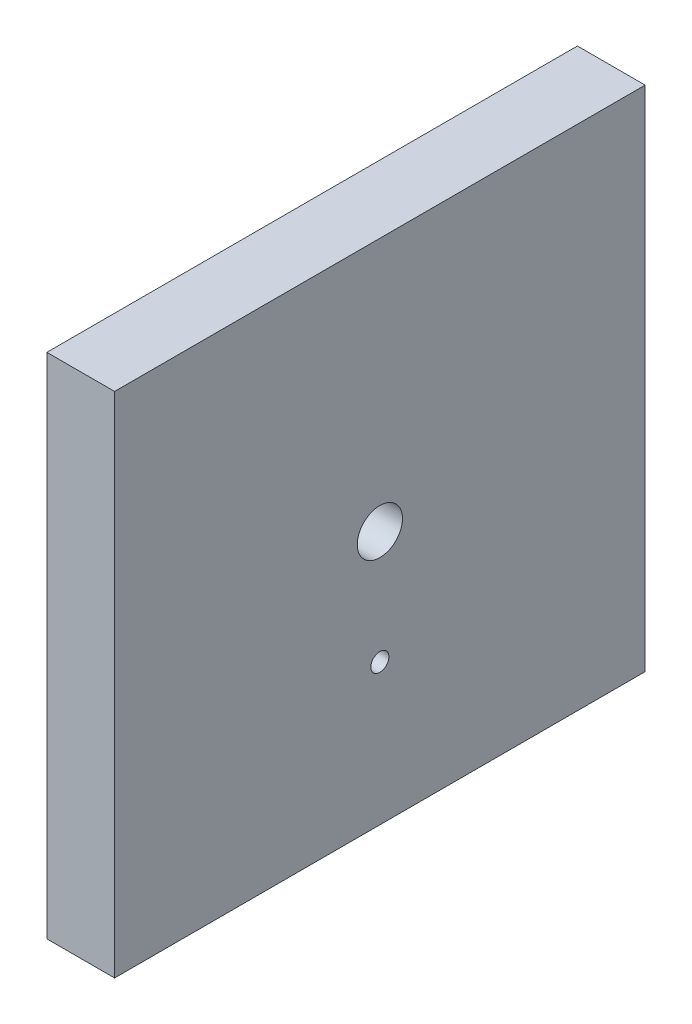
SolidWorks part; units mm, degrees
ref_plane "Ebene vorne" through (0, 0, 0) normal (0, 0, 1) x (1, 0, 0)
ref_plane "Ebene oben" through (0, 0, 0) normal (0, 1, 0) x (1, 0, 0)
ref_plane "Ebene rechts" through (0, 0, 0) normal (1, 0, 0) x (0, 0, -1)
sketch "Sketch1" plane through (0, 0, 0) normal (1, 0, 0) x (0, 0, -1)
  line L0 (0, 39.4227) -> (0, -41.65) construction
  line L1 (-47, 45) -> (47, 45)
  line L2 (-47, 45) -> (-47, -45)
  line L3 (-47, -45) -> (47, -45)
  line L4 (47, 45) -> (47, -45)
  line L5 (48.1091, 0) -> (-28.5091, 0) construction
  dimension "D1" = 94
  dimension "D2" = 90
extrude "Boss-Extrude1" add sketch "Sketch1" along normal blind 12
sketch "Sketch2" plane through (12, 0, 0) normal (1, 0, 0) x (0, 0, -1)
  circle A0 centre (0, 0) radius 4
  dimension "D1" = 8
extrude "Cut-Extrude1" cut sketch "Sketch2" against normal through all
sketch "Sketch3" plane through (0, 0, 0) normal (-1, 0, 0) x (0, 0, 1)
  circle A0 centre (0, -20) radius 1.6
  dimension "D1" = 3.2
extrude "Cut-Extrude2" cut sketch "Sketch3" against normal through all
